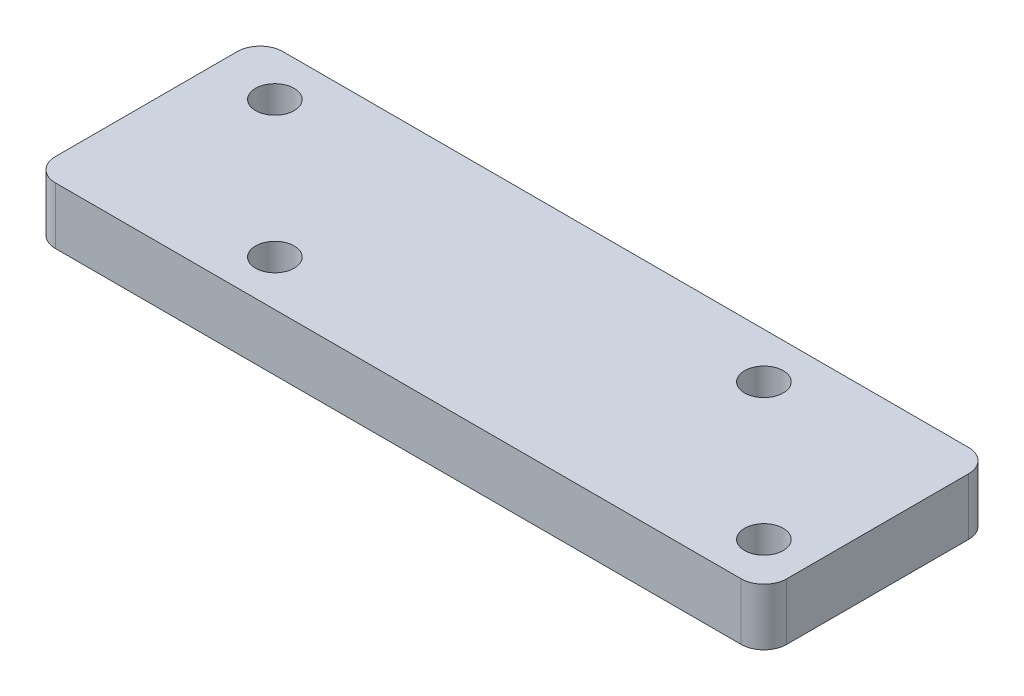
SolidWorks part; units mm, degrees
ref_plane "前视基准面" through (0, 0, 0) normal (0, 0, 1) x (1, 0, 0)
ref_plane "上视基准面" through (0, 0, 0) normal (0, 1, 0) x (1, 0, 0)
ref_plane "右视基准面" through (0, 0, 0) normal (1, 0, 0) x (0, 0, -1)
sketch "草图1" plane through (0, 0, 0) normal (0, 1, 0) x (1, 0, 0)
  line L0 (5.3, 16) -> (48.3, 16) construction
  line L1 (0, 0) -> (64.3, 0)
  line L2 (0, 0) -> (0, 20)
  line L3 (0, 20) -> (64.3, 20)
  line L4 (64.3, 0) -> (64.3, 20)
  circle A0 centre (5.3, 16) radius 1.7
  circle A1 centre (17.3, 4) radius 1.7
  circle A2 centre (48.3, 16) radius 1.7
  circle A3 centre (60.3, 4) radius 1.7
  dimension "D1" = 3.4
  dimension "D2" = 5.3
  dimension "D4" = 12
  dimension "D5" = 4
  dimension "D6" = 12
  dimension "D3" = 20
  dimension "D7" = 64.3
  dimension "D9" = 43
  dimension "D8" = 2
extrude "凸台-拉伸1" add sketch "草图1" along normal blind 5
fillet "圆角1" radius 2 4 edges at (0, 2.5, 0) (0, 2.5, -20) (64.3, 2.5, -20) (64.3, 2.5, 0)
